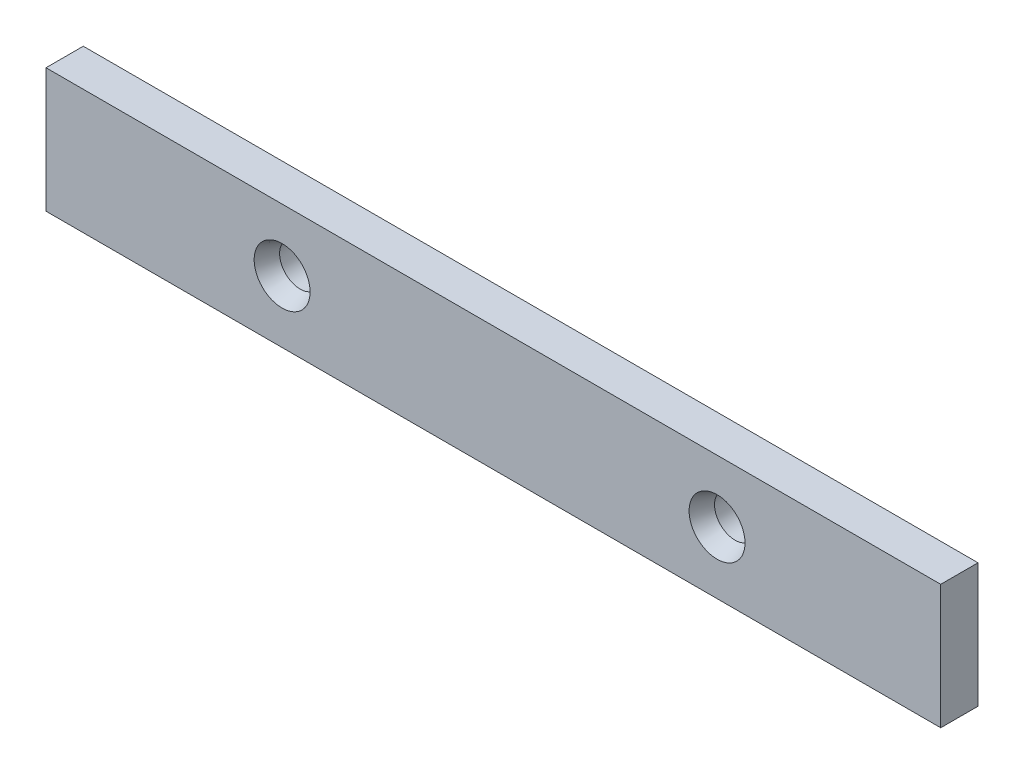
SolidWorks part; units mm, degrees
ref_plane "Front Plane" through (0, 0, 0) normal (0, 0, 1) x (1, 0, 0)
ref_plane "Top Plane" through (0, 0, 0) normal (0, 1, 0) x (1, 0, 0)
ref_plane "Right Plane" through (0, 0, 0) normal (1, 0, 0) x (0, 0, -1)
sketch "Sketch1" plane through (0, 0, 0) normal (0, 0, 1) x (1, 0, 0)
  line L1 (0, 0) -> (144, 0)
  line L2 (0, 0) -> (0, 20)
  line L3 (0, 20) -> (144, 20)
  line L4 (144, 0) -> (144, 20)
extrude "Extrude1" add sketch "Sketch1" along normal blind 6
hole_wizard "CSK for M6 Flat Head Machine Screw4" positions "3DSketch7" profile "Sketch9" countersink size "M6" standard "Ansi Metric" end condition through all
sketch3d "3DSketch7"
  line L0 (0, 0, 6) -> (144, 0, 6) construction
  line L2 (144, 0, 6) -> (144, 20, 6) construction
  point P0 (38, 10, 6)
  point P2 (108, 10, 6)
  dimension "D1" = 70
  dimension "D2" = 10
  dimension "D3" = 10
  dimension "D4" = 36
sketch "Sketch9" plane through (38, 10, 6) normal (1, 0, 0) x (0, -1, 0)
  line L0 (0, 0) -> (0, 6)
  line L1 (0, 6) -> (3.3, 6)
  line L2 (3.3, 6) -> (3.3, 2.8971)
  line L3 (3.3, 2.8971) -> (4.5, 0)
  line L5 (4.5, 0) -> (0, 0)
  line L6 (-3.3, 2.8971) -> (-4.5, 0) construction
  line L11 (0, -6.35) -> (0, 107.95) construction
  dimension "Thru Hole Dia." = 6.6
  dimension "Thru Hole Depth" = 6
  dimension "Near C'Sink Dia." = 9
  dimension "Near C'Sink Angle" = 45
